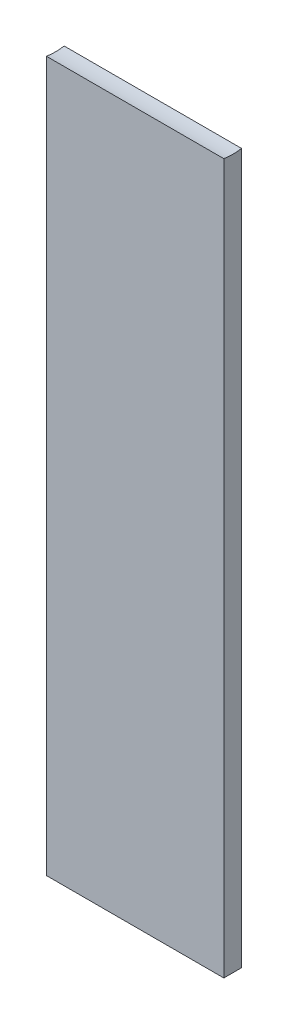
SolidWorks part; units mm, degrees
ref_plane "Front Plane" through (0, 0, 0) normal (0, 0, 1) x (1, 0, 0)
ref_plane "Top Plane" through (0, 0, 0) normal (0, 1, 0) x (1, 0, 0)
ref_plane "Right Plane" through (0, 0, 0) normal (1, 0, 0) x (0, 0, -1)
sketch "Sketch1" plane through (0, 0, 0) normal (0, 1, 0) x (1, 0, 0)
  line L1 (6.35, -0.635) -> (-6.35, -0.635)
  line L2 (6.35, -0.635) -> (6.35, 0.635)
  line L3 (6.35, 0.635) -> (-6.35, 0.635)
  line L4 (-6.35, -0.635) -> (-6.35, 0.635)
  line L5 (6.35, -0.635) -> (-6.35, 0.635) construction
  line L6 (6.35, 0.635) -> (-6.35, -0.635) construction
  point P0 (0, 0)
  dimension "D1" = 12.7
  dimension "D2" = 1.27
extrude "Boss-Extrude1" add sketch "Sketch1" along normal blind 50.8
sketch "Sketch4" plane through (6.35, 0, 0) normal (1, 0, 0) x (0, 0, -1)
  circle A1 centre (0, 54.5567) radius 3.81
extrude "Cut-Extrude1" cut sketch "Sketch4" against normal blind 50.8
